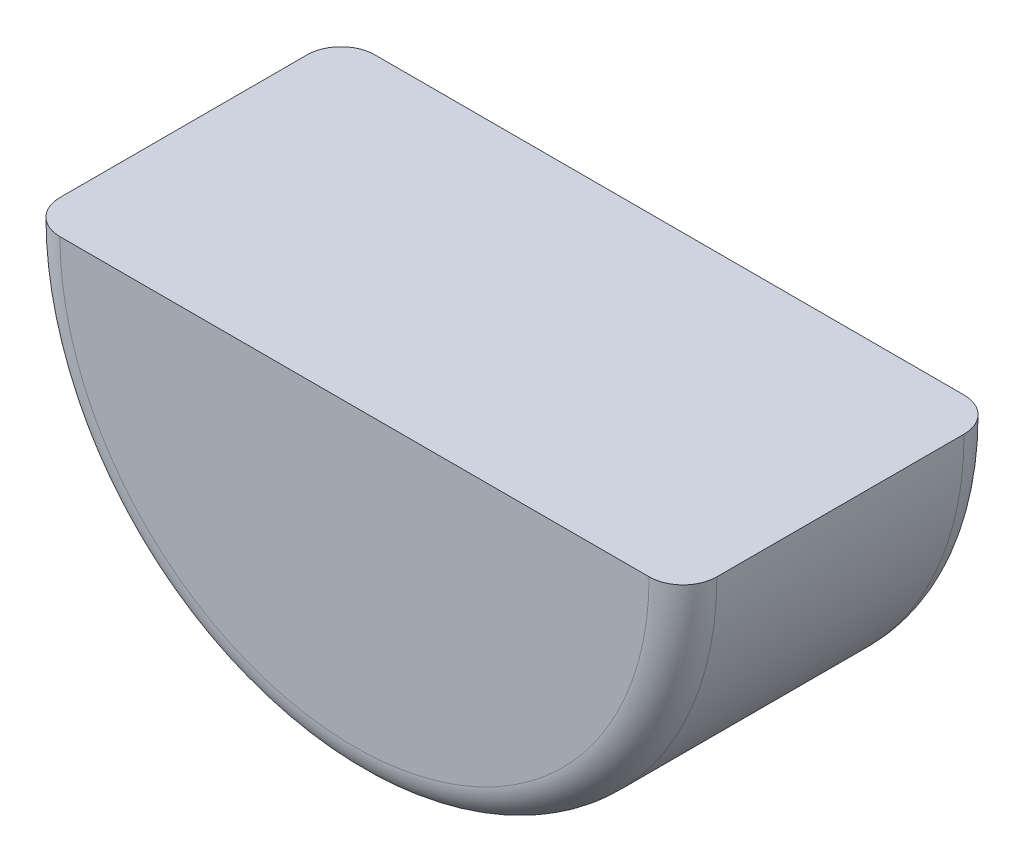
SolidWorks part; units mm, degrees
ref_plane "Plan de face" through (0, 0, 0) normal (0, 0, 1) x (1, 0, 0)
ref_plane "Plan de dessus" through (0, 0, 0) normal (0, 1, 0) x (1, 0, 0)
ref_plane "Plan de droite" through (0, 0, 0) normal (1, 0, 0) x (0, 0, -1)
sketch "Esquisse1" plane through (0, 0, 0) normal (0, 1, 0) x (1, 0, 0)
  line L0 (0, -46.5) -> (0, 46.5)
  line L1 (0, 46.5) -> (87, 46.5)
  line L2 (97, 36.5) -> (97, -36.5)
  line L3 (87, -46.5) -> (0, -46.5)
  arc A0 (97, 36.5) -> (87, 46.5) centre (87, 36.5) ccw
  arc A1 (97, -36.5) -> (87, -46.5) centre (87, -36.5) cw
  point P4 (0, 0)
  point P10 (0, 0)
  dimension "D1" = 10
  dimension "D2" = 10
revolve "Révolution1" add sketch "Esquisse1" angle 180 about L0
sketch "Esquisse4" plane through (0, 0, 0) normal (0, 1, 0) x (1, 0, 0)
  line L0 (94.0149, 20.11) -> (94.0149, -19.89)
  line L1 (79.5811, 45.11) -> (-40.9851, 45.11)
  line L2 (79.5811, 45.11) -> (94.0149, 20.11)
  line L3 (94.0149, -19.89) -> (79.5811, -44.89)
  line L4 (79.5811, -44.89) -> (-40.9851, -44.89)
  arc A0 (-40.9851, -44.89) -> (-95.0684, 0.11) centre (-40.9851, 10.11) cw
  arc A1 (-95.0684, 0.11) -> (-40.9851, 45.11) centre (-40.9851, -9.89) cw
curve "Courbe comp.2"
